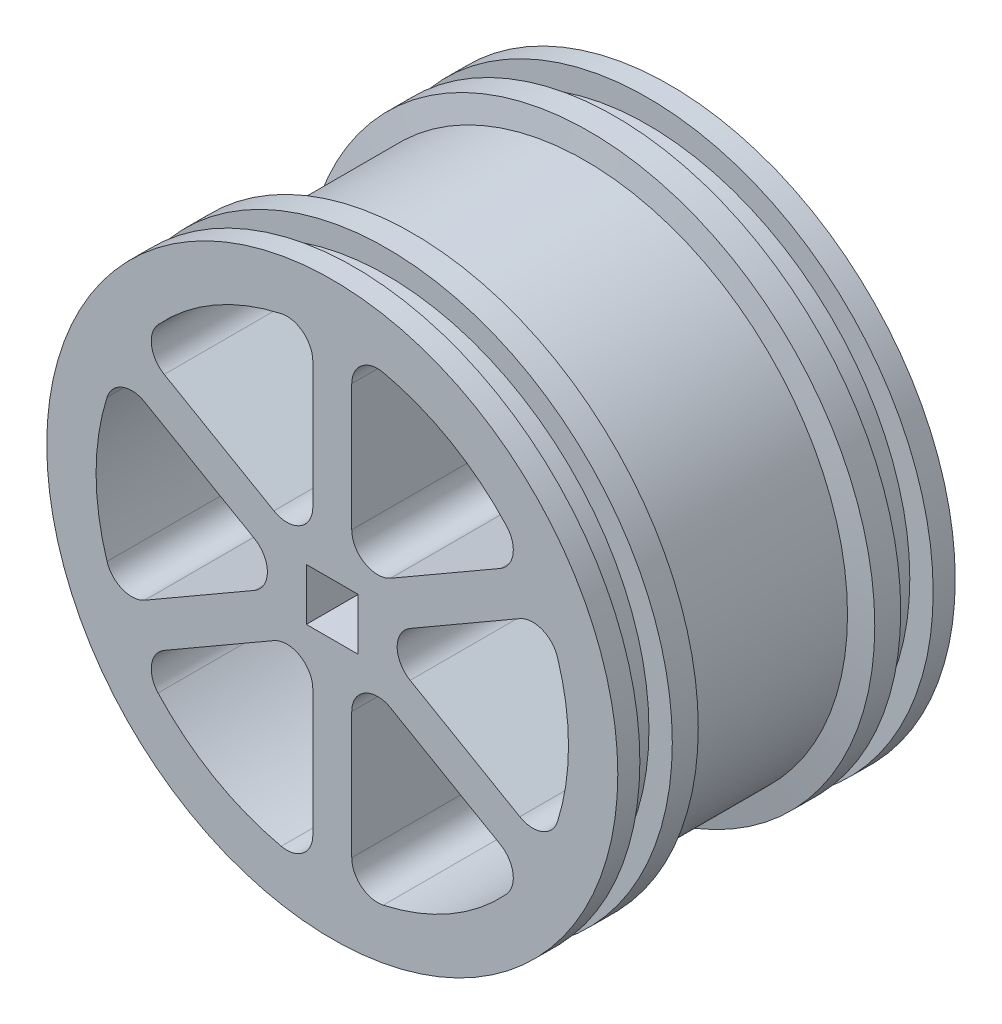
SolidWorks part; units mm, degrees
ref_plane "Front Plane" through (0, 0, 0) normal (0, 0, 1) x (1, 0, 0)
ref_plane "Top Plane" through (0, 0, 0) normal (0, 1, 0) x (1, 0, 0)
ref_plane "Right Plane" through (0, 0, 0) normal (1, 0, 0) x (0, 0, -1)
sketch "Sketch1" plane through (0, 0, 0) normal (1, 0, 0) x (0, 0, -1)
  line L1 (0, 22) -> (1.7, 22)
  line L2 (1.7, 22) -> (1.7, 20.2)
  line L3 (1.7, 20.2) -> (4.2, 20.2)
  line L4 (4.2, 20.2) -> (4.2, 22)
  line L5 (4.2, 22) -> (6.2, 22)
  line L6 (6.2, 22) -> (6.5, 20.2)
  line L7 (19.8, 22) -> (19.5, 20.2)
  line L8 (19.5, 20.2) -> (6.5, 20.2)
  line L10 (0, 18.2) -> (26, 18.2)
  line L11 (19.8, 22) -> (21.8, 22)
  line L12 (21.8, 22) -> (21.8, 20.2)
  line L13 (21.8, 20.2) -> (24.3, 20.2)
  line L14 (24.3, 20.2) -> (24.3, 22)
  line L15 (24.3, 22) -> (26, 22)
  line L18 (-0.3222, 0) -> (27.2819, 0) construction
  line L19 (0, 0) -> (0, 18.2) construction
  line L20 (0, 22) -> (0, 1028.7814) construction
  line L21 (0, 22) -> (0, 18.2)
  line L22 (26, 22) -> (26, 18.2)
  dimension "D1" = 22
  dimension "D2" = 1.7
  dimension "D3" = 2
  dimension "D4" = 0.3
  dimension "D5" = 2.3
  dimension "D6" = 3.8
  dimension "D7" = 1.8
  dimension "D8" = 2.5
  dimension "D9" = 26
revolve "Revolve1" add sketch "Sketch1" angle 360 about L18
sketch "Sketch2" plane through (0, 0, 0) normal (0, 0, 1) x (1, 0, 0)
  line L0 (0, 0) -> (0, 18.2) construction
  line L1 (-1.5, 18.2) -> (-1.5, 0)
  line L2 (-1.5, 18.2) -> (1.5, 18.2)
  line L3 (-1.5, 0) -> (1.5, 0)
  line L4 (1.5, 18.2) -> (1.5, 0)
  line L5 (-1.5, 18.2) -> (1.5, 0) construction
  line L6 (-1.5, 0) -> (1.5, 18.2) construction
  circle A0 centre (0, 0) radius 18.2 construction
  point P6 (0, 9.1)
  dimension "D1" = 18.2
  dimension "D2" = 3
extrude "Boss-Extrude1" add sketch "Sketch2" against normal blind 26
pattern_circular "CirPattern1" count 6 over 360 about axis through (0, 0, 0) along (0, 0, 1) of "Boss-Extrude1"
sketch "Sketch3" plane through (0, 0, 0) normal (0, 0, 1) x (1, 0, 0)
  line L1 (-2, -2) -> (2, -2)
  line L2 (-2, -2) -> (-2, 2)
  line L3 (-2, 2) -> (2, 2)
  line L4 (2, -2) -> (2, 2)
  line L5 (-2, -2) -> (2, 2) construction
  line L6 (-2, 2) -> (2, -2) construction
  point P0 (0, 0)
  dimension "D1" = 4
extrude "Cut-Extrude1" cut sketch "Sketch3" against normal through all both and the other way through all
fillet "Fillet1" radius 2 18 edges at (3, 0, -13) (1.5, -2.5981, -13) (-1.5, -2.5981, -13) (-3, 0, -13) (16.458, 7.77, -13) (14.958, 10.3681, -13) (16.458, -7.77, -13) (14.958, -10.3681, -13) (-14.958, 10.3681, -13) (-1.5, -18.1381, -13) (1.5, -18.1381, -13) (-16.458, -7.77, -13) (-14.958, -10.3681, -13) (-16.458, 7.77, -13) (1.5, 18.1381, -13) (-1.5, 18.1381, -13) (-1.5, 2.5981, -13) (1.5, 2.5981, -13)
